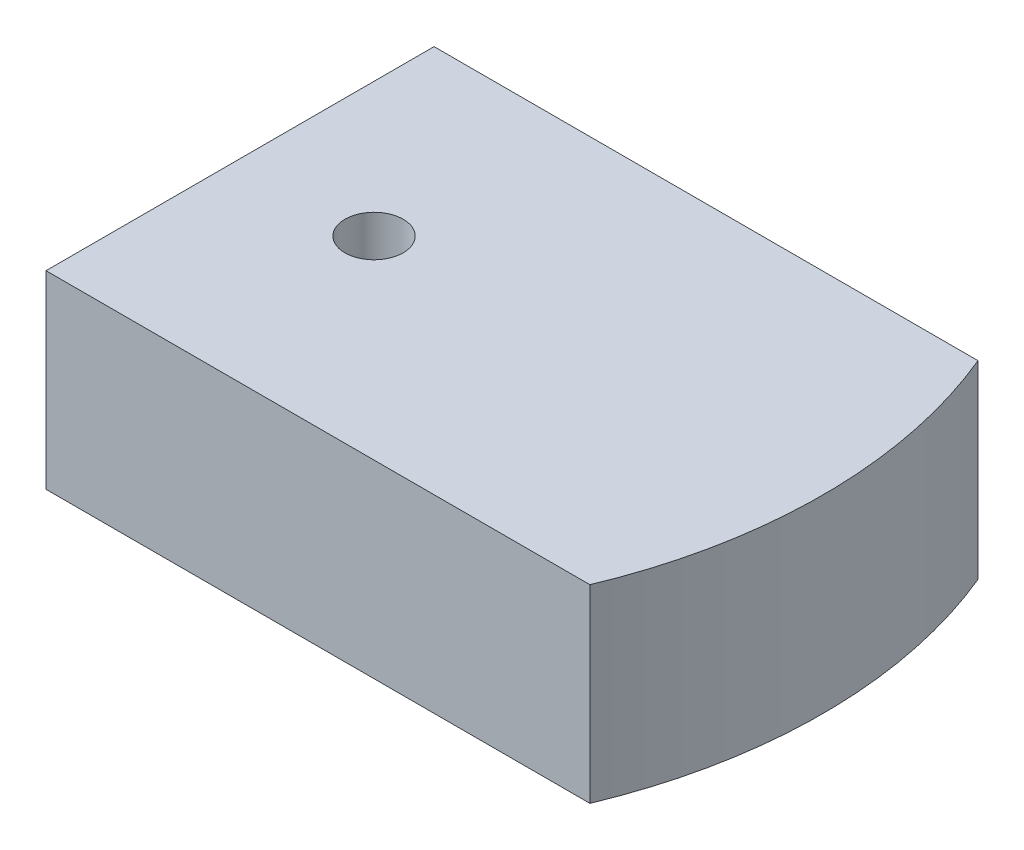
SolidWorks part; units mm, degrees
ref_plane "Front Plane" through (0, 0, 0) normal (0, 0, 1) x (1, 0, 0)
ref_plane "Top Plane" through (0, 0, 0) normal (0, 1, 0) x (1, 0, 0)
ref_plane "Right Plane" through (0, 0, 0) normal (1, 0, 0) x (0, 0, -1)
sketch "Sketch1" plane through (0, 0, 0) normal (0, 1, 0) x (1, 0, 0)
  line L0 (0, 0) -> (17.6424, 0) construction
  line L1 (0, 8.4582) -> (23.7099, 8.4582)
  line L2 (0, 8.4582) -> (0, -8.4582)
  line L3 (0, -8.4582) -> (23.7099, -8.4582)
  line L4 (23.7099, 8.4582) -> (23.7099, -8.4582) construction
  arc A0 (23.7099, 8.4582) -> (23.7099, -8.4582) centre (3.39, 0) cw
  circle A1 centre (5.842, 0) radius 1.27
  dimension "D3" = 2.54
  dimension "D1" = 25.4
  dimension "D2" = 16.9164
  dimension "D4" = 5.842
  dimension "D5" = 23.7099
extrude "Boss-Extrude1" add sketch "Sketch1" along normal blind 8.255
